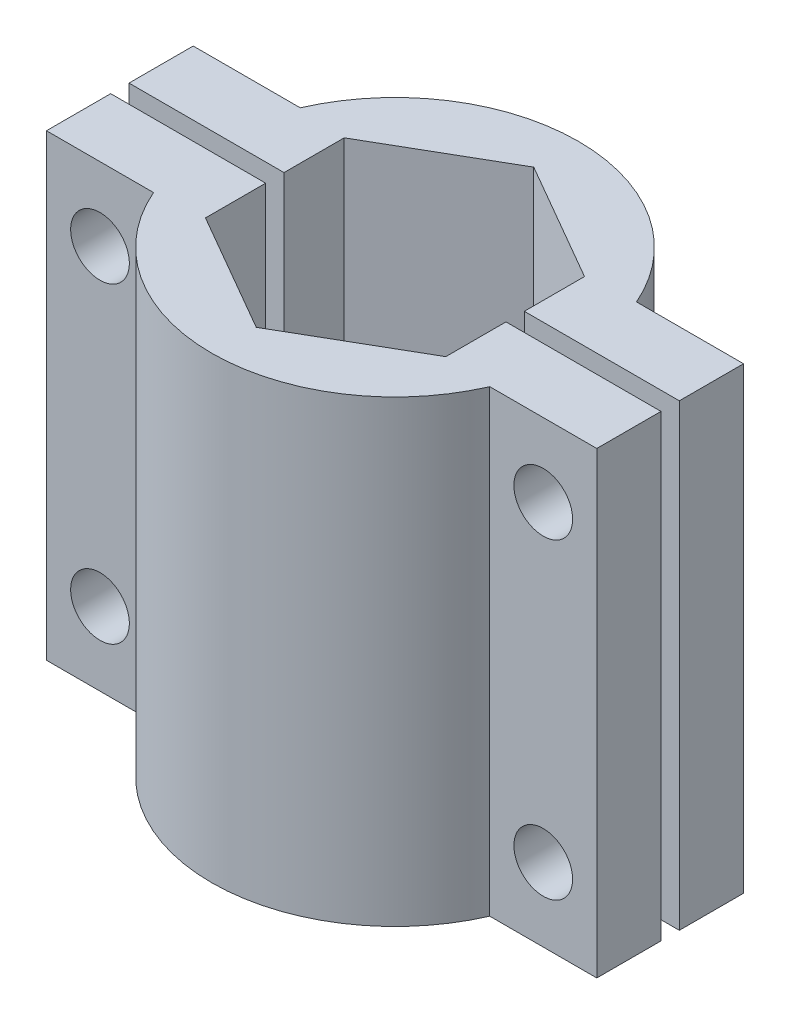
SolidWorks part; units mm, degrees
ref_plane "正面" through (0, 0, 0) normal (0, 0, 1) x (1, 0, 0)
ref_plane "平面" through (0, 0, 0) normal (0, 1, 0) x (1, 0, 0)
ref_plane "右側面" through (0, 0, 0) normal (1, 0, 0) x (0, 0, -1)
sketch "ｽｹｯﾁ1" plane through (0, 0, 0) normal (0, 1, 0) x (1, 0, 0)
  line L0 (9.1652, 4) -> (15, 4)
  line L1 (-15, -4) -> (-9.1652, -4)
  line L2 (-15, -4) -> (-15, 4)
  line L3 (-15, 4) -> (-9.1652, 4)
  line L4 (15, -4) -> (15, 4)
  line L5 (-15, -4) -> (15, 4) construction
  line L6 (-15, 4) -> (15, -4) construction
  line L7 (9.1652, -4) -> (15, -4)
  arc A0 (9.1652, 4) -> (-9.1652, 4) centre (0, 0) ccw
  arc A1 (-9.1652, -4) -> (9.1652, -4) centre (0, 0) ccw
  dimension "D1" = 10
  dimension "D2" = 30
  dimension "D3" = 8
extrude "ﾎﾞｽ - 押し出し1" add sketch "ｽｹｯﾁ1" along normal blind 25
sketch "ｽｹｯﾁ2" plane through (0, 0, 0) normal (0, -1, 0) x (1, 0, 0)
  line L0 (1.7471, 2.5) -> (-1.7471, 2.5)
  arc A0 (-1.7471, 2.5) -> (1.7471, 2.5) centre (0, 0) ccw
  dimension "D2" = 3.05
  dimension "D1" = 2.5
extrude "ｶｯﾄ - 押し出し1" cut sketch "ｽｹｯﾁ2" against normal blind 12.5
sketch "ｽｹｯﾁ3" plane through (0, 25, 0) normal (0, 1, 0) x (1, 0, 0)
  line L1 (0, -7.5633) -> (6.55, -3.7816)
  line L2 (6.55, -3.7816) -> (6.55, 3.7816)
  line L3 (6.55, 3.7816) -> (0, 7.5633)
  line L4 (0, 7.5633) -> (-6.55, 3.7816)
  line L5 (-6.55, 3.7816) -> (-6.55, -3.7816)
  line L6 (-6.55, -3.7816) -> (0, -7.5633)
  circle A0 centre (0, 0) radius 6.55 construction
  point P1 (7.5056, 0)
  point P10 (3.7445, 6.5048)
  dimension "D1" = 13.1
extrude "ｶｯﾄ - 押し出し2" cut sketch "ｽｹｯﾁ3" against normal blind 12.5
sketch "ｽｹｯﾁ4" plane through (0, 0, 0) normal (0, 1, 0) x (1, 0, 0)
  line L0 (15, -4) -> (15, 4) construction
  line L1 (-15, -0.5) -> (15, -0.5)
  line L2 (-15, -0.5) -> (-15, 0.5)
  line L3 (-15, 0.5) -> (15, 0.5)
  line L4 (15, -0.5) -> (15, 0.5)
  line L5 (-15, -0.5) -> (15, 0.5) construction
  line L6 (-15, 0.5) -> (15, -0.5) construction
  line L7 (-15, 4) -> (-15, -4) construction
  point P0 (0, 0)
  point P8 (0, 0)
  dimension "D1" = 1
extrude "ｶｯﾄ - 押し出し3" cut sketch "ｽｹｯﾁ4" along normal through all
sketch "ｽｹｯﾁ5" plane through (0, 0, 0) normal (0, 0, 1) x (1, 0, 0)
  line L0 (-12.0826, 25) -> (-12.0826, 0) construction
  line L1 (-15, 25) -> (-9.1652, 25) construction
  line L2 (-15, 0) -> (-9.1652, 0) construction
  line L3 (12.0826, 25) -> (12.0826, 0) construction
  line L4 (9.1652, 25) -> (15, 25) construction
  line L5 (9.1652, 0) -> (15, 0) construction
  circle A0 centre (-12.0826, 21) radius 1.6
  circle A1 centre (12.0826, 21) radius 1.6
  circle A2 centre (-12.0826, 4) radius 1.6
  circle A3 centre (12.0826, 4) radius 1.6
  point P20 (0, 0)
  point P21 (0, 0)
  point P22 (0, 0)
  dimension "D1" = 3.2
  dimension "D2" = 4
  dimension "D3" = 4
extrude "ｶｯﾄ - 押し出し4" cut sketch "ｽｹｯﾁ5" against normal through all both and the other way through all
